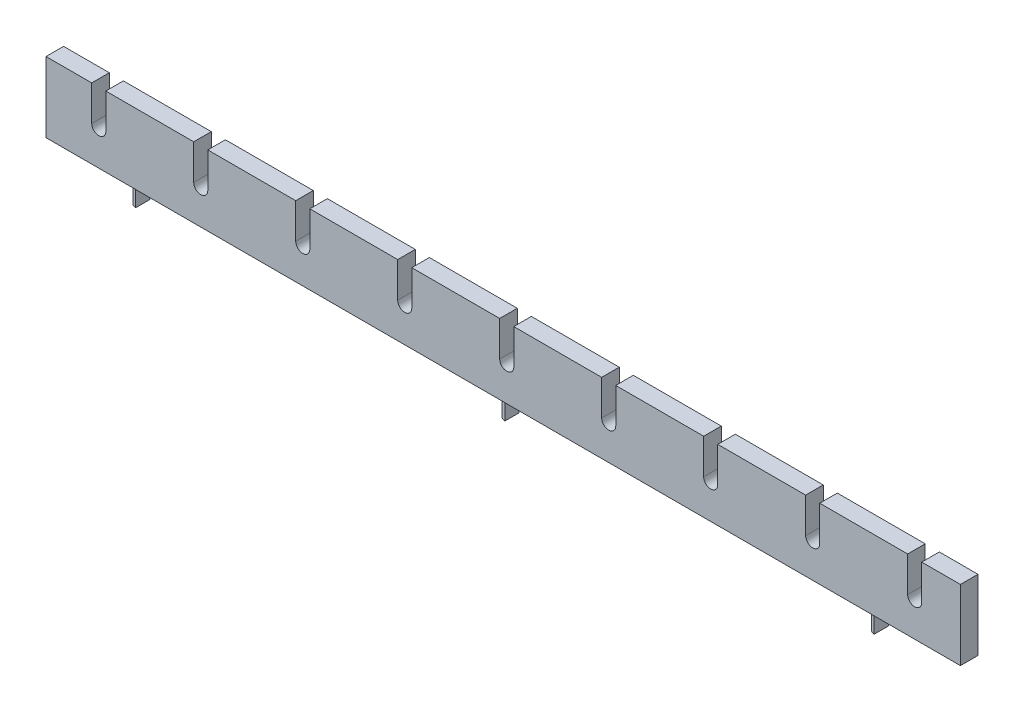
SolidWorks part; units mm, degrees
material "PPE"
ref_plane "Front Plane" through (0, 0, 0) normal (0, 0, 1) x (1, 0, 0)
ref_plane "Top Plane" through (0, 0, 0) normal (0, 1, 0) x (1, 0, 0)
ref_plane "Right Plane" through (0, 0, 0) normal (1, 0, 0) x (0, 0, -1)
sketch "Sketch1" plane through (0, 0, 0) normal (0, 1, 0) x (1, 0, 0)
  line L1 (-165.1, -3.175) -> (165.1, -3.175)
  line L2 (-165.1, -3.175) -> (-165.1, 3.175)
  line L3 (-165.1, 3.175) -> (165.1, 3.175)
  line L4 (165.1, -3.175) -> (165.1, 3.175)
  line L5 (-165.1, -3.175) -> (165.1, 3.175) construction
  line L6 (-165.1, 3.175) -> (165.1, -3.175) construction
  point P0 (0, 0)
  dimension "D1" = 6.35
  dimension "D2" = 330.2
extrude "Boss-Extrude1" add sketch "Sketch1" along normal blind 25.4 contours L2 L3 L4 L1
sketch "Sketch2" plane through (0, 0, 0) normal (0, -1, 0) x (1, 0, 0)
  line L0 (-133.35, 2.54) -> (-133.35, -2.54)
  line L1 (0, 2.54) -> (0, -2.54)
  line L2 (133.35, 2.54) -> (133.35, -2.54)
  line L3 (-165.1, 3.175) -> (-165.1, -3.175) construction
  arc A1 (-133.35, 2.54) -> (-133.35, -2.54) centre (-133.35, 0) ccw
  arc A2 (0, 2.54) -> (0, -2.54) centre (0, 0) ccw
  arc A3 (133.35, 2.54) -> (133.35, -2.54) centre (133.35, 0) ccw
  dimension "D1" = 5.08
  dimension "D2" = 3
  dimension "D4" = 31.75
extrude "Boss-Extrude2" add sketch "Sketch2" along normal blind 6.35
sketch "Sketch3" plane through (0, 0, 3.175) normal (0, 0, 1) x (1, 0, 0)
  line L0 (-146.05, 38.1) -> (-146.05, 12.7) construction
  line L1 (-165.1, 25.4) -> (165.1, 25.4) construction
  line L2 (-143.51, 38.1) -> (-143.51, 12.7)
  line L3 (-148.59, 38.1) -> (-148.59, 12.7)
  line L4 (-109.22, 38.1) -> (-109.22, 12.7) construction
  line L5 (-106.68, 38.1) -> (-106.68, 12.7)
  line L6 (-111.76, 38.1) -> (-111.76, 12.7)
  line L7 (-72.39, 38.1) -> (-72.39, 12.7) construction
  line L8 (-69.85, 38.1) -> (-69.85, 12.7)
  line L9 (-74.93, 38.1) -> (-74.93, 12.7)
  line L10 (-35.56, 38.1) -> (-35.56, 12.7) construction
  line L11 (-33.02, 38.1) -> (-33.02, 12.7)
  line L12 (-38.1, 38.1) -> (-38.1, 12.7)
  line L13 (1.27, 38.1) -> (1.27, 12.7) construction
  line L14 (3.81, 38.1) -> (3.81, 12.7)
  line L15 (-1.27, 38.1) -> (-1.27, 12.7)
  line L16 (38.1, 38.1) -> (38.1, 12.7) construction
  line L17 (40.64, 38.1) -> (40.64, 12.7)
  line L18 (35.56, 38.1) -> (35.56, 12.7)
  line L19 (74.93, 38.1) -> (74.93, 12.7) construction
  line L20 (77.47, 38.1) -> (77.47, 12.7)
  line L21 (72.39, 38.1) -> (72.39, 12.7)
  line L22 (111.76, 38.1) -> (111.76, 12.7) construction
  line L23 (114.3, 38.1) -> (114.3, 12.7)
  line L24 (109.22, 38.1) -> (109.22, 12.7)
  line L25 (148.59, 38.1) -> (148.59, 12.7) construction
  line L26 (151.13, 38.1) -> (151.13, 12.7)
  line L27 (146.05, 38.1) -> (146.05, 12.7)
  line L28 (-165.1, 25.4) -> (-165.1, 0) construction
  arc A0 (-143.51, 38.1) -> (-148.59, 38.1) centre (-146.05, 38.1) ccw
  arc A1 (-148.59, 12.7) -> (-143.51, 12.7) centre (-146.05, 12.7) ccw
  arc A2 (-106.68, 38.1) -> (-111.76, 38.1) centre (-109.22, 38.1) ccw
  arc A3 (-111.76, 12.7) -> (-106.68, 12.7) centre (-109.22, 12.7) ccw
  arc A4 (-69.85, 38.1) -> (-74.93, 38.1) centre (-72.39, 38.1) ccw
  arc A5 (-74.93, 12.7) -> (-69.85, 12.7) centre (-72.39, 12.7) ccw
  arc A6 (-33.02, 38.1) -> (-38.1, 38.1) centre (-35.56, 38.1) ccw
  arc A7 (-38.1, 12.7) -> (-33.02, 12.7) centre (-35.56, 12.7) ccw
  arc A8 (3.81, 38.1) -> (-1.27, 38.1) centre (1.27, 38.1) ccw
  arc A9 (-1.27, 12.7) -> (3.81, 12.7) centre (1.27, 12.7) ccw
  arc A10 (40.64, 38.1) -> (35.56, 38.1) centre (38.1, 38.1) ccw
  arc A11 (35.56, 12.7) -> (40.64, 12.7) centre (38.1, 12.7) ccw
  arc A12 (77.47, 38.1) -> (72.39, 38.1) centre (74.93, 38.1) ccw
  arc A13 (72.39, 12.7) -> (77.47, 12.7) centre (74.93, 12.7) ccw
  arc A14 (114.3, 38.1) -> (109.22, 38.1) centre (111.76, 38.1) ccw
  arc A15 (109.22, 12.7) -> (114.3, 12.7) centre (111.76, 12.7) ccw
  arc A16 (151.13, 38.1) -> (146.05, 38.1) centre (148.59, 38.1) ccw
  arc A17 (146.05, 12.7) -> (151.13, 12.7) centre (148.59, 12.7) ccw
  point P4 (-146.05, 25.4)
  point P14 (-109.22, 25.4)
  point P21 (-72.39, 25.4)
  point P28 (-35.56, 25.4)
  point P35 (1.27, 25.4)
  point P42 (38.1, 25.4)
  point P49 (74.93, 25.4)
  point P56 (111.76, 25.4)
  point P63 (148.59, 25.4)
  dimension "D1" = 5.08
  dimension "D2" = 12.7
  dimension "D3" = 19.05
  dimension "D5" = 31.75
  dimension "D6" = 36.83
  dimension "D4" = 9
extrude "Cut-Extrude1" cut sketch "Sketch3" against normal through all
